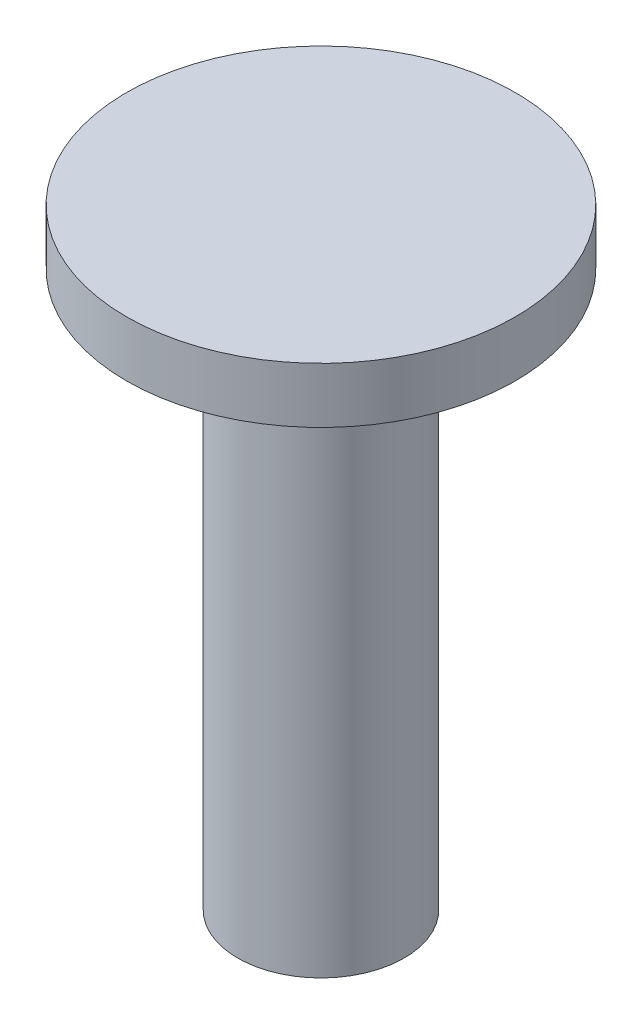
SolidWorks part; units mm, degrees
material "AISI 304"
ref_plane "前视基准面" through (0, 0, 0) normal (0, 0, 1) x (1, 0, 0)
ref_plane "上视基准面" through (0, 0, 0) normal (0, 1, 0) x (1, 0, 0)
ref_plane "右视基准面" through (0, 0, 0) normal (1, 0, 0) x (0, 0, -1)
other "Configuration Table"
sketch "草图1" plane through (0, 0, 0) normal (0, 1, 0) x (1, 0, 0)
  circle A0 centre (0, 0) radius 3.5
  dimension "D1" = 7
extrude "凸台-拉伸1" add sketch "草图1" along normal blind 1
sketch "草图2" plane through (0, 0, 0) normal (0, -1, 0) x (1, 0, 0)
  circle A0 centre (0, 0) radius 1.5
  dimension "D1" = 3
extrude "凸台-拉伸2" add sketch "草图2" along normal blind 10
